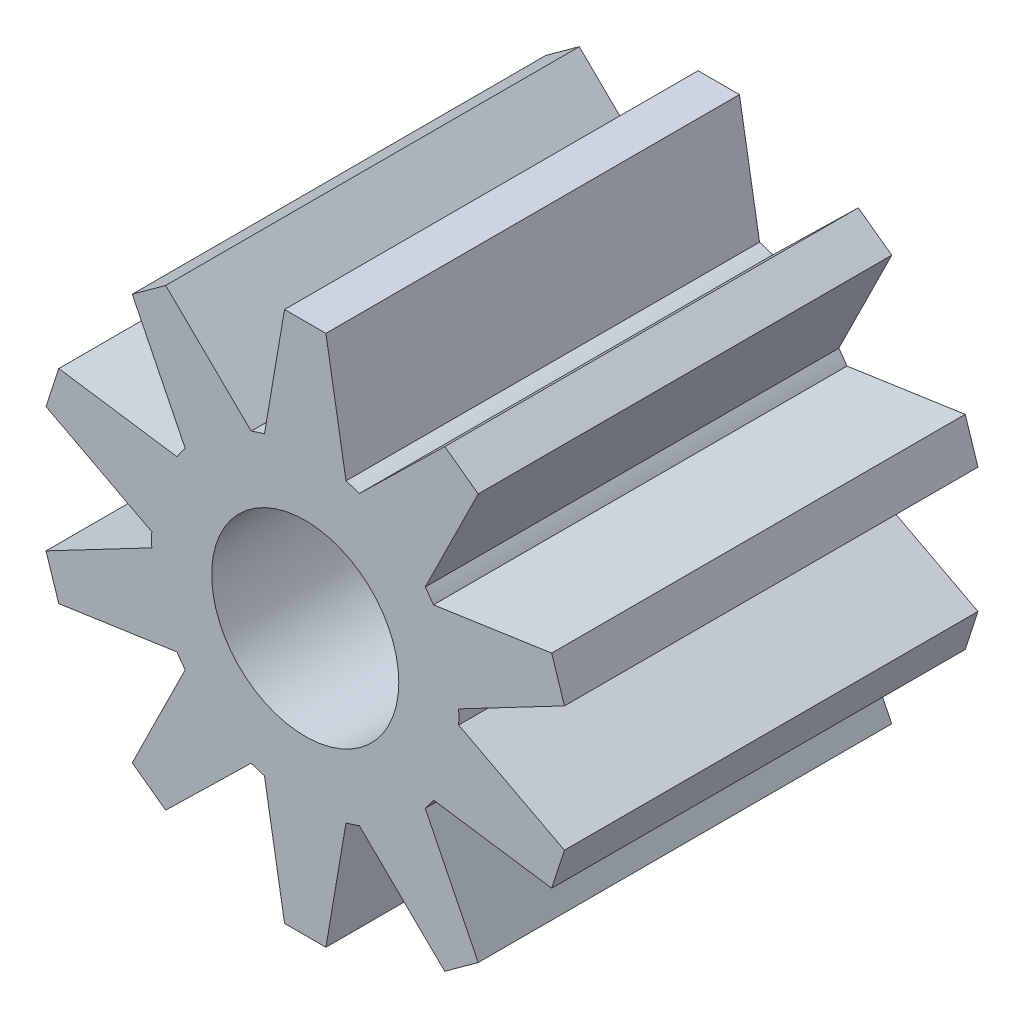
SolidWorks part; units mm, degrees
material "ABS"
ref_plane "Front Plane" through (0, 0, 0) normal (0, 0, 1) x (1, 0, 0)
ref_plane "Top Plane" through (0, 0, 0) normal (0, 1, 0) x (1, 0, 0)
ref_plane "Right Plane" through (0, 0, 0) normal (1, 0, 0) x (0, 0, -1)
sketch "Sketch1" plane through (0, 0, 0) normal (0, 0, 1) x (1, 0, 0)
  line L0 (-0.2223, 2.8575) -> (0.2223, 2.8575)
  line L1 (-0.4381, 1.5918) -> (0.4381, 1.5918)
  line L2 (1.8594, 2.1811) -> (1.2901, 1.0303)
  line L3 (-0.2223, 2.8575) -> (-0.4381, 1.5918)
  line L4 (0.2223, 2.8575) -> (0.4381, 1.5918)
  line L5 (0.5812, 1.5453) -> (1.2901, 1.0303)
  line L6 (1.4998, 2.4424) -> (0.5812, 1.5453)
  line L7 (1.4998, 2.4424) -> (1.8594, 2.1811)
  line L8 (2.7863, 0.6716) -> (1.6493, 0.0752)
  line L9 (1.3785, 0.9086) -> (1.6493, 0.0752)
  line L10 (2.649, 1.0944) -> (1.3785, 0.9086)
  line L11 (2.649, 1.0944) -> (2.7863, 0.6716)
  line L12 (2.649, -1.0944) -> (1.3785, -0.9086)
  line L13 (1.6493, -0.0752) -> (1.3785, -0.9086)
  line L14 (2.7863, -0.6716) -> (1.6493, -0.0752)
  line L15 (2.7863, -0.6716) -> (2.649, -1.0944)
  line L16 (1.4998, -2.4424) -> (0.5812, -1.5453)
  line L17 (1.2901, -1.0303) -> (0.5812, -1.5453)
  line L18 (1.8594, -2.1811) -> (1.2901, -1.0303)
  line L19 (1.8594, -2.1811) -> (1.4998, -2.4424)
  line L20 (-0.2222, -2.8575) -> (-0.4381, -1.5918)
  line L21 (0.4382, -1.5918) -> (-0.4381, -1.5918)
  line L22 (0.2223, -2.8575) -> (0.4382, -1.5918)
  line L23 (0.2223, -2.8575) -> (-0.2222, -2.8575)
  line L24 (-1.8594, -2.1811) -> (-1.2901, -1.0303)
  line L25 (-0.5812, -1.5453) -> (-1.2901, -1.0303)
  line L26 (-1.4998, -2.4424) -> (-0.5812, -1.5453)
  line L27 (-1.4998, -2.4424) -> (-1.8594, -2.1811)
  line L28 (-2.7863, -0.6716) -> (-1.6493, -0.0752)
  line L29 (-1.3785, -0.9086) -> (-1.6493, -0.0752)
  line L30 (-2.649, -1.0944) -> (-1.3785, -0.9086)
  line L31 (-2.649, -1.0944) -> (-2.7863, -0.6716)
  line L32 (-2.649, 1.0944) -> (-1.3785, 0.9086)
  line L33 (-1.6493, 0.0752) -> (-1.3785, 0.9086)
  line L34 (-2.7863, 0.6716) -> (-1.6493, 0.0752)
  line L35 (-2.7863, 0.6716) -> (-2.649, 1.0944)
  line L36 (-1.4998, 2.4424) -> (-0.5812, 1.5453)
  line L37 (-1.2901, 1.0303) -> (-0.5812, 1.5453)
  line L38 (-1.8594, 2.1811) -> (-1.2901, 1.0303)
  line L39 (-1.8594, 2.1811) -> (-1.4998, 2.4424)
  circle A0 centre (0, 0) radius 2.8575 construction
  circle A1 centre (0, 0) radius 1.651
  point P8 (0, 2.8575)
  point P11 (0, 1.5918)
  point P50 (0, 0)
  dimension "D1" = 5.715
  dimension "D3" = 0.8763
  dimension "D4" = 0.4445
  dimension "D2" = 1.2065
  dimension "D5" = 10
extrude "Boss-Extrude1" add sketch "Sketch1" along normal blind 4.445 contours L9 A1 L5 L1 L37 L33 L29 L25 L21 L17 L13 | A1 L2 L7 L6 | A1 L4 L0 L3 | A1 L36 L39 L38 | A1 L32 L35 L34 | A1 L28 L31 L30 | A1 L24 L27 L26 | A1 L20 L23 L22 | A1 L16 L19 L18 | A1 L12 L15 L14 | A1 L8 L11 L10
sketch "Sketch2" plane through (0, 0, 4.445) normal (0, 0, 1) x (1, 0, 0)
  circle A0 centre (0, 0) radius 1.0058
  dimension "D1" = 2.0117
extrude "Cut-Extrude1" cut sketch "Sketch2" against normal through all
